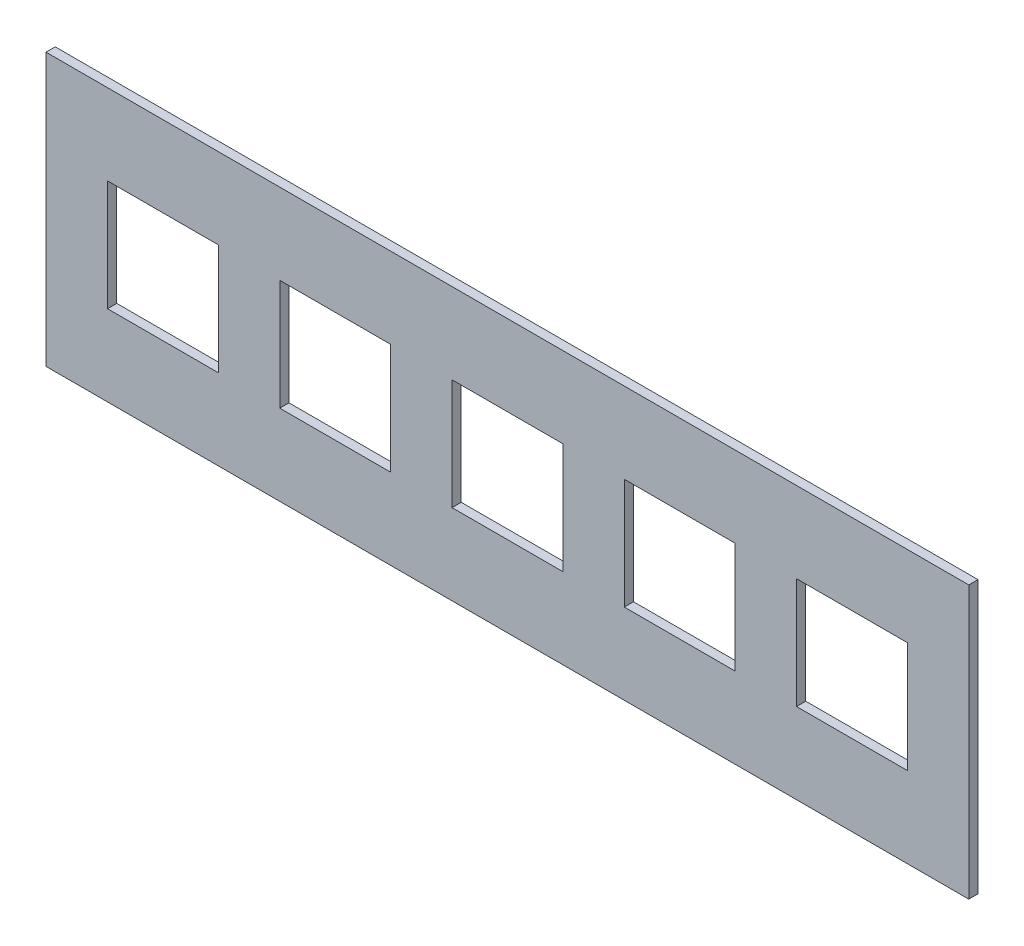
SolidWorks part; units mm, degrees
ref_plane "Front Plane" through (0, 0, 0) normal (0, 0, 1) x (1, 0, 0)
ref_plane "Top Plane" through (0, 0, 0) normal (0, 1, 0) x (1, 0, 0)
ref_plane "Right Plane" through (0, 0, 0) normal (1, 0, 0) x (0, 0, -1)
sketch "Sketch1" plane through (0, 0, 0) normal (0, 0, 1) x (1, 0, 0)
  line L0 (-74, 18) -> (-74, -18)
  line L1 (-150, -44.24) -> (150, -44.24)
  line L2 (-150, -44.24) -> (-150, 44.24)
  line L3 (-150, 44.24) -> (150, 44.24)
  line L4 (150, -44.24) -> (150, 44.24)
  line L5 (-150, -44.24) -> (150, 44.24) construction
  line L6 (-150, 44.24) -> (150, -44.24) construction
  line L7 (-130, 18) -> (-94, 18)
  line L8 (-130, 18) -> (-130, -18)
  line L9 (-130, -18) -> (-94, -18)
  line L10 (-94, 18) -> (-94, -18)
  line L11 (-74, 18) -> (-38, 18)
  line L12 (-38, 18) -> (-38, -18)
  line L13 (-74, -18) -> (-38, -18)
  line L14 (-18, 18) -> (-18, -18)
  line L15 (-18, 18) -> (18, 18)
  line L16 (18, 18) -> (18, -18)
  line L17 (-18, -18) -> (18, -18)
  line L18 (38, 18) -> (38, -18)
  line L19 (38, 18) -> (74, 18)
  line L20 (74, 18) -> (74, -18)
  line L21 (38, -18) -> (74, -18)
  line L22 (94, 18) -> (94, -18)
  line L23 (94, 18) -> (130, 18)
  line L24 (130, 18) -> (130, -18)
  line L25 (94, -18) -> (130, -18)
  line L26 (-130, 18) -> (-74, 18) construction
  point P0 (0, 0)
  point P10 (-94, 0)
  dimension "D1" = 36
  dimension "D2" = 36
  dimension "D3" = 20
  dimension "D5" = 56
  dimension "D6" = 20
  dimension "D7" = 88.48
  dimension "D8" = 300
  dimension "D4" = 5
extrude "Boss-Extrude1" add sketch "Sketch1" along normal blind 3
